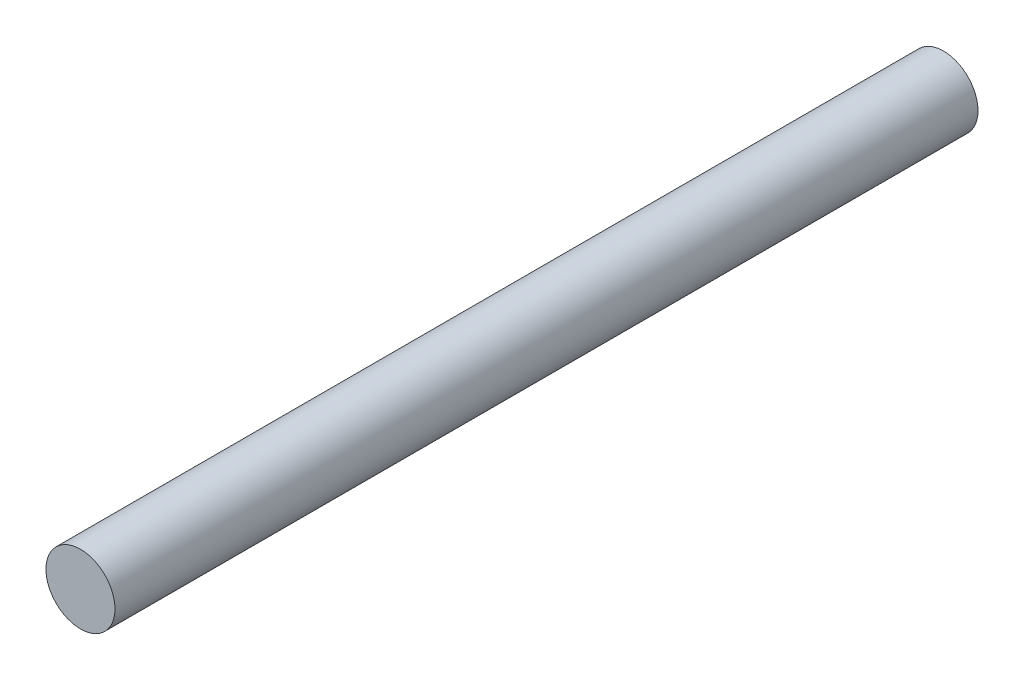
SolidWorks part; units mm, degrees
ref_plane "Front Plane" through (0, 0, 0) normal (0, 0, 1) x (1, 0, 0)
ref_plane "Top Plane" through (0, 0, 0) normal (0, 1, 0) x (1, 0, 0)
ref_plane "Right Plane" through (0, 0, 0) normal (1, 0, 0) x (0, 0, -1)
sketch "Sketch1" plane through (0, 0, 0) normal (0, 0, 1) x (1, 0, 0)
  circle A0 centre (0, 0) radius 4
  dimension "D1" = 8
extrude "Boss-Extrude1" add sketch "Sketch1" along normal blind 100
sketch "Sketch2" plane through (0, 0, 0) normal (0, 1, 0) x (1, 0, 0)
  point P0 (0, -49.9619)
